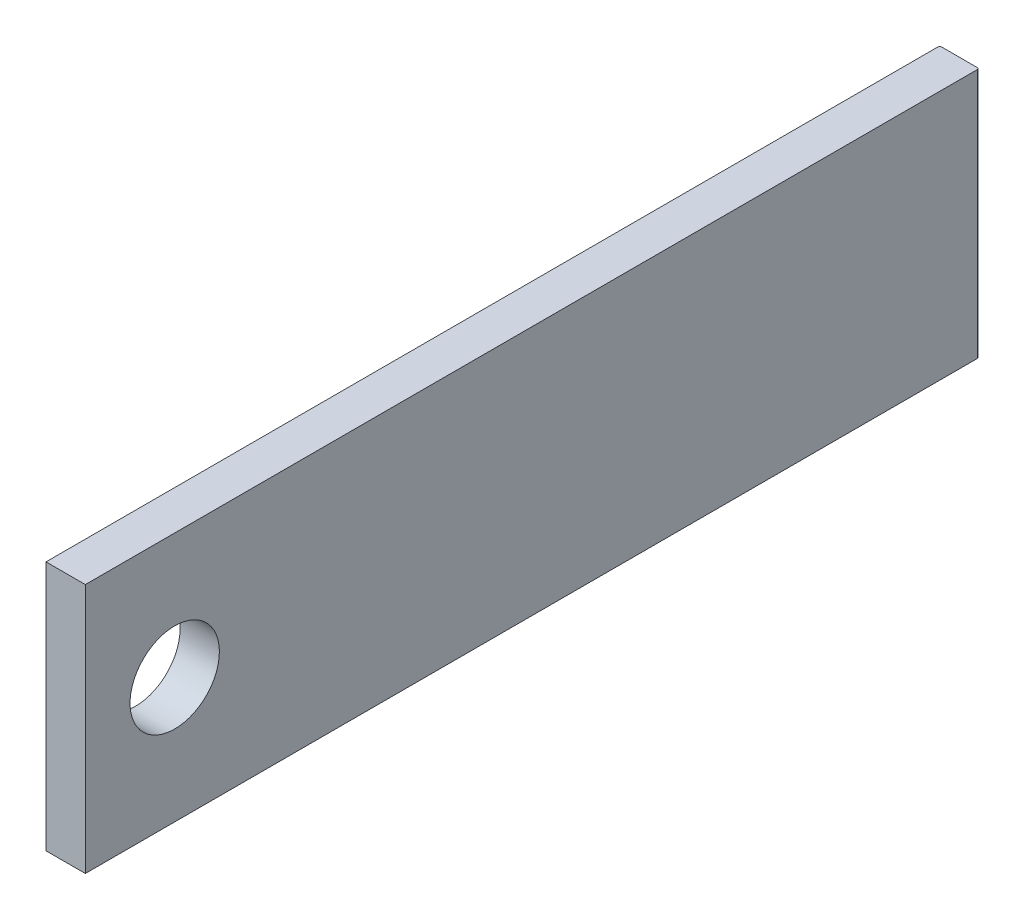
SolidWorks part; units mm, degrees
ref_plane "Front Plane" through (0, 0, 0) normal (0, 0, 1) x (1, 0, 0)
ref_plane "Top Plane" through (0, 0, 0) normal (0, 1, 0) x (1, 0, 0)
ref_plane "Right Plane" through (0, 0, 0) normal (1, 0, 0) x (0, 0, -1)
sketch "Sketch1" plane through (0, 0, 0) normal (1, 0, 0) x (0, 0, -1)
  line L1 (-25, 7) -> (25, 7)
  line L2 (-25, 7) -> (-25, -7)
  line L3 (-25, -7) -> (25, -7)
  line L4 (25, 7) -> (25, -7)
  line L5 (-25, 7) -> (25, -7) construction
  line L6 (-25, -7) -> (25, 7) construction
  point P1 (0, 0)
  dimension "D1" = 14
  dimension "D2" = 50
extrude "Boss-Extrude1" add sketch "Sketch1" along normal blind 2.2
sketch "Sketch2" plane through (2.2, 0, 0) normal (1, 0, 0) x (0, 0, -1)
  line L1 (-25, 7) -> (-25, -7) construction
  line L2 (-27.4378, 0) -> (-22.5, 0) construction
  circle A0 centre (-20, 0) radius 2.5
  dimension "D2" = 5
  dimension "D3" = 5
extrude "Cut-Extrude1" cut sketch "Sketch2" against normal through all
fillet "Fillet1" radius 0.1 1 edges at (2.2, 0, -25)
fillet "Fillet2" radius 0.1 1 edges at (0, 0, -25)
